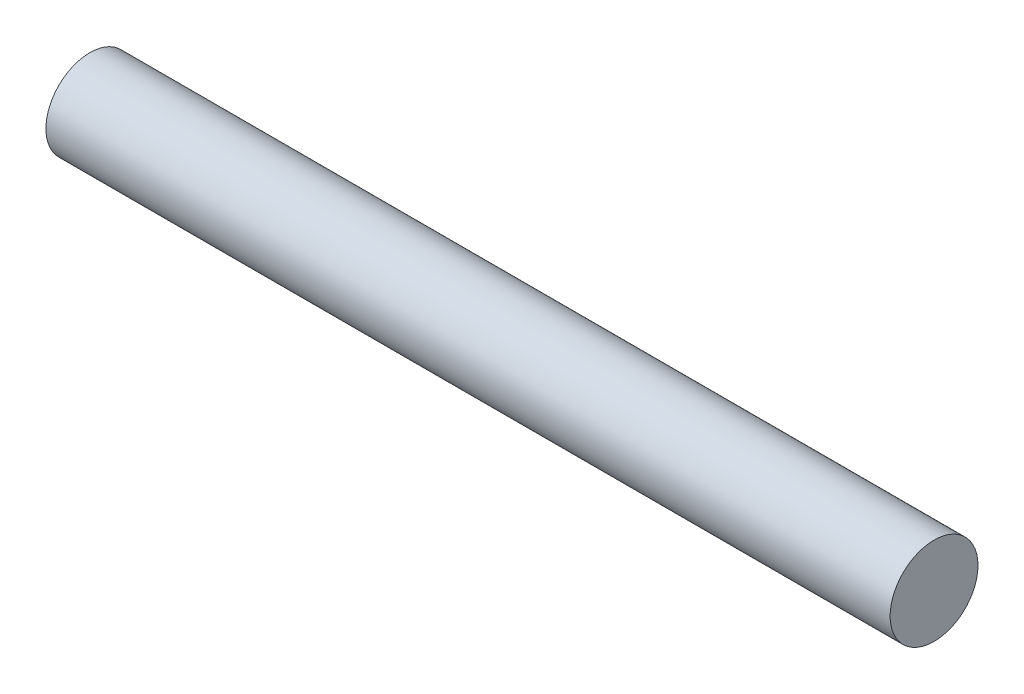
SolidWorks part; units mm, degrees
ref_plane "Front Plane" through (0, 0, 0) normal (0, 0, 1) x (1, 0, 0)
ref_plane "Top Plane" through (0, 0, 0) normal (0, 1, 0) x (1, 0, 0)
ref_plane "Right Plane" through (0, 0, 0) normal (1, 0, 0) x (0, 0, -1)
sketch "Sketch2" plane through (0, 0, 0) normal (1, 0, 0) x (0, 0, -1)
  circle A0 centre (0, 0) radius 3.85
  dimension "D1" = 7.7
extrude "Boss-Extrude1" add sketch "Sketch2" along normal mid plane 74
